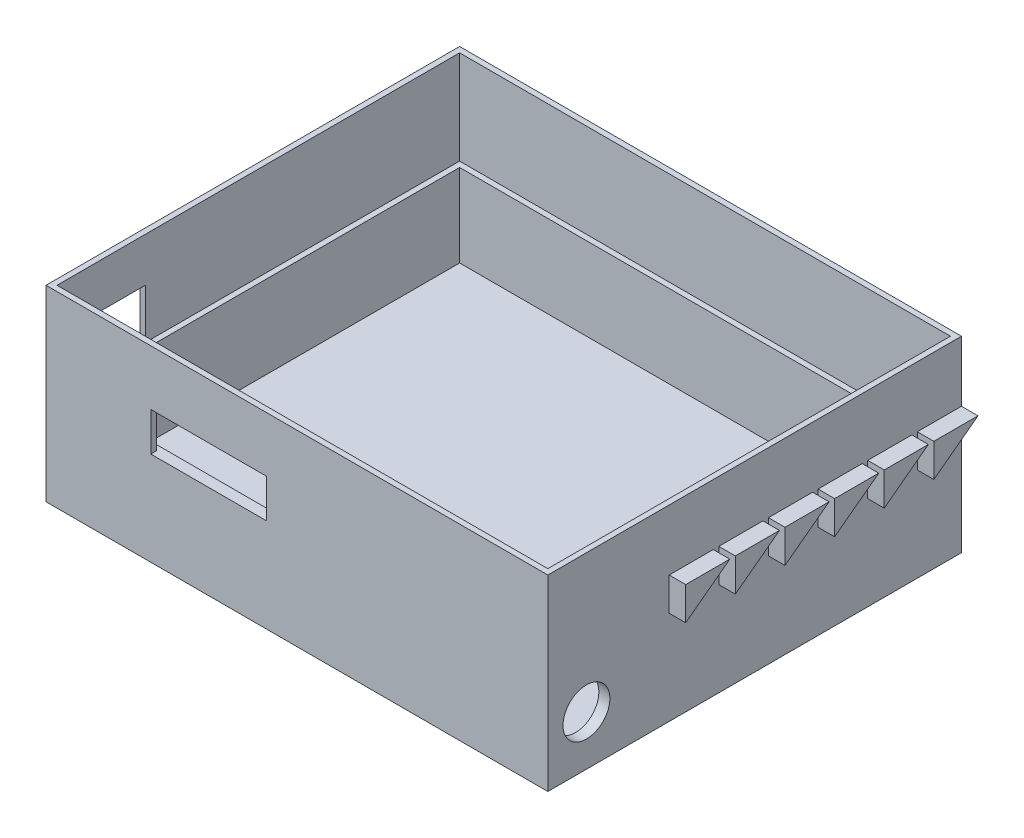
SolidWorks part; units mm, degrees
ref_plane "前视基准面" through (0, 0, 0) normal (0, 0, 1) x (1, 0, 0)
ref_plane "上视基准面" through (0, 0, 0) normal (0, 1, 0) x (1, 0, 0)
ref_plane "右视基准面" through (0, 0, 0) normal (1, 0, 0) x (0, 0, -1)
sketch "草图1" plane through (0, 0, 0) normal (0, 1, 0) x (1, 0, 0)
  line L1 (-43.5, 35.5) -> (43.5, 35.5)
  line L2 (-43.5, 35.5) -> (-43.5, -35.5)
  line L3 (-43.5, -35.5) -> (43.5, -35.5)
  line L4 (43.5, 35.5) -> (43.5, -35.5)
  line L5 (-43.5, 35.5) -> (43.5, -35.5) construction
  line L6 (-43.5, -35.5) -> (43.5, 35.5) construction
  point P0 (0, 0)
  dimension "D1" = 87
  dimension "D2" = 71
extrude "凸台-拉伸1" add sketch "草图1" along normal blind 2
sketch "草图2" plane through (0, 0, 0) normal (0, 1, 0) x (1, 0, 0)
  line L1 (-43.5, 35.5) -> (43.5, 35.5)
  line L2 (-43.5, 35.5) -> (-43.5, -35.5)
  line L3 (-43.5, -35.5) -> (43.5, -35.5)
  line L4 (43.5, 35.5) -> (43.5, -35.5)
  line L5 (-45.5, 37.5) -> (45.5, 37.5)
  line L6 (-45.5, 37.5) -> (-45.5, -37.5)
  line L7 (-45.5, -37.5) -> (45.5, -37.5)
  line L8 (45.5, 37.5) -> (45.5, -37.5)
  line L9 (-45.5, 37.5) -> (45.5, -37.5) construction
  line L10 (-45.5, -37.5) -> (45.5, 37.5) construction
  point P6 (0, 0)
  dimension "D1" = 91
  dimension "D2" = 75
extrude "凸台-拉伸2" add sketch "草图2" along normal blind 17
ref_plane "基准面1" through (45.5, 0, 0) normal (1, 0, 0) x (0, 0, -1)
sketch "草图3" plane through (45.5, 0, 0) normal (1, 0, 0) x (0, 0, -1)
  line L0 (-37.5, 17) -> (-37.5, 0) construction
  line L1 (-37.5, 17) -> (37.5, 17) construction
  circle A0 centre (-30.5, 9) radius 4.25
  dimension "D1" = 8.5
  dimension "D3" = 8
  dimension "D2" = 7
extrude "切除-拉伸2" cut sketch "草图3" against normal blind 17
ref_plane "基准面2" through (0, 17, 0) normal (0, 1, 0) x (1, 0, 0)
sketch "草图4" plane through (0, 17, 0) normal (0, 1, 0) x (1, 0, 0)
  line L1 (-45.5, 37.5) -> (45.5, 37.5)
  line L2 (-45.5, 37.5) -> (-45.5, -37.5)
  line L3 (-45.5, -37.5) -> (45.5, -37.5)
  line L4 (45.5, 37.5) -> (45.5, -37.5)
  line L5 (-45.5, 37.5) -> (45.5, -37.5) construction
  line L6 (-45.5, -37.5) -> (45.5, 37.5) construction
  line L7 (-44.5, 36.5) -> (44.5, 36.5)
  line L8 (-44.5, 36.5) -> (-44.5, -36.5)
  line L9 (-44.5, -36.5) -> (44.5, -36.5)
  line L10 (44.5, 36.5) -> (44.5, -36.5)
  line L11 (-44.5, 36.5) -> (44.5, -36.5) construction
  line L12 (-44.5, -36.5) -> (44.5, 36.5) construction
  point P0 (0, 0)
  point P7 (0, 0)
  dimension "D1" = 73
  dimension "D2" = 89
extrude "凸台-拉伸3" add sketch "草图4" along normal blind 17
ref_plane "基准面3" through (-44.5, 0, 0) normal (1, 0, 0) x (0, 0, -1)
ref_plane "基准面4" through (-45.5, 0, 0) normal (-1, 0, 0) x (0, 0, 1)
sketch "草图6" plane through (-45.5, 0, 0) normal (-1, 0, 0) x (0, 0, 1)
  line L0 (40.15, 17) -> (-40.15, 17) construction
  line L1 (36.5, 26) -> (20.5, 26)
  line L2 (36.5, 26) -> (36.5, 17)
  line L3 (36.5, 17) -> (20.5, 17)
  line L4 (20.5, 26) -> (20.5, 17)
  line L5 (37.5, 34) -> (37.5, 0) construction
  dimension "D1" = 1
  dimension "D2" = 16
  dimension "D3" = 9
extrude "切除-拉伸3" cut sketch "草图6" against normal blind 17
ref_plane "基准面5" through (0, 0, 37.5) normal (0, 0, 1) x (1, 0, 0)
sketch "草图7" plane through (0, 0, 37.5) normal (0, 0, 1) x (1, 0, 0)
  line L0 (40.15, 17) -> (-40.15, 17) construction
  line L1 (-26.5, 24) -> (-5.5, 24)
  line L2 (-26.5, 24) -> (-26.5, 17)
  line L3 (-26.5, 17) -> (-5.5, 17)
  line L4 (-5.5, 24) -> (-5.5, 17)
  line L5 (-45.5, 18.7) -> (-45.5, -18.7) construction
  dimension "D1" = 21
  dimension "D2" = 7
  dimension "D3" = 19
extrude "切除-拉伸4" cut sketch "草图7" against normal blind 17
sketch "草图8" plane through (-45.5, 0, 0) normal (-1, 0, 0) x (0, 0, 1)
  line L0 (-37.5, 17) -> (-37.5, 23)
  line L1 (-37.5, 34) -> (-37.5, 0) construction
  line L2 (-37.5, 23) -> (-29.5, 23)
  line L3 (-29.5, 23) -> (-37.5, 17)
  line L4 (-20.5, 23) -> (-28.5, 17)
  line L5 (-28.5, 17) -> (-28.5, 23)
  line L6 (-28.5, 23) -> (-20.5, 23)
  line L7 (-11.5, 23) -> (-19.5, 17)
  line L8 (-19.5, 17) -> (-19.5, 23)
  line L9 (-19.5, 23) -> (-11.5, 23)
  line L10 (-2.5, 23) -> (-10.5, 17)
  line L11 (-10.5, 17) -> (-10.5, 23)
  line L12 (-10.5, 23) -> (-2.5, 23)
  line L13 (6.5, 23) -> (-1.5, 17)
  line L14 (-1.5, 17) -> (-1.5, 23)
  line L15 (-1.5, 23) -> (6.5, 23)
  line L16 (15.5, 23) -> (7.5, 17)
  line L17 (7.5, 17) -> (7.5, 23)
  line L18 (7.5, 23) -> (15.5, 23)
  dimension "D1" = 8
  dimension "D2" = 6
  dimension "D3" = 6
extrude "凸台-拉伸4" add sketch "草图8" along normal blind 3
sketch "草图9" plane through (45.5, 0, 0) normal (1, 0, 0) x (0, 0, -1)
  line L0 (37.5, 23) -> (29.5, 23)
  line L1 (37.5, 34) -> (37.5, 0) construction
  line L2 (29.5, 23) -> (29.5, 17)
  line L3 (40.7, 17) -> (-40.7, 17) construction
  line L4 (29.5, 17) -> (37.5, 23)
  line L5 (20.5, 17) -> (28.5, 23)
  line L6 (28.5, 23) -> (20.5, 23)
  line L7 (20.5, 23) -> (20.5, 17)
  line L8 (11.5, 17) -> (19.5, 23)
  line L9 (19.5, 23) -> (11.5, 23)
  line L10 (11.5, 23) -> (11.5, 17)
  line L11 (2.5, 17) -> (10.5, 23)
  line L12 (10.5, 23) -> (2.5, 23)
  line L13 (2.5, 23) -> (2.5, 17)
  line L14 (-6.5, 17) -> (1.5, 23)
  line L15 (1.5, 23) -> (-6.5, 23)
  line L16 (-6.5, 23) -> (-6.5, 17)
  line L17 (-15.5, 17) -> (-7.5, 23)
  line L18 (-7.5, 23) -> (-15.5, 23)
  line L19 (-15.5, 23) -> (-15.5, 17)
  dimension "D1" = 8
  dimension "D2" = 6
  dimension "D3" = 6
extrude "凸台-拉伸5" add sketch "草图9" along normal blind 3
